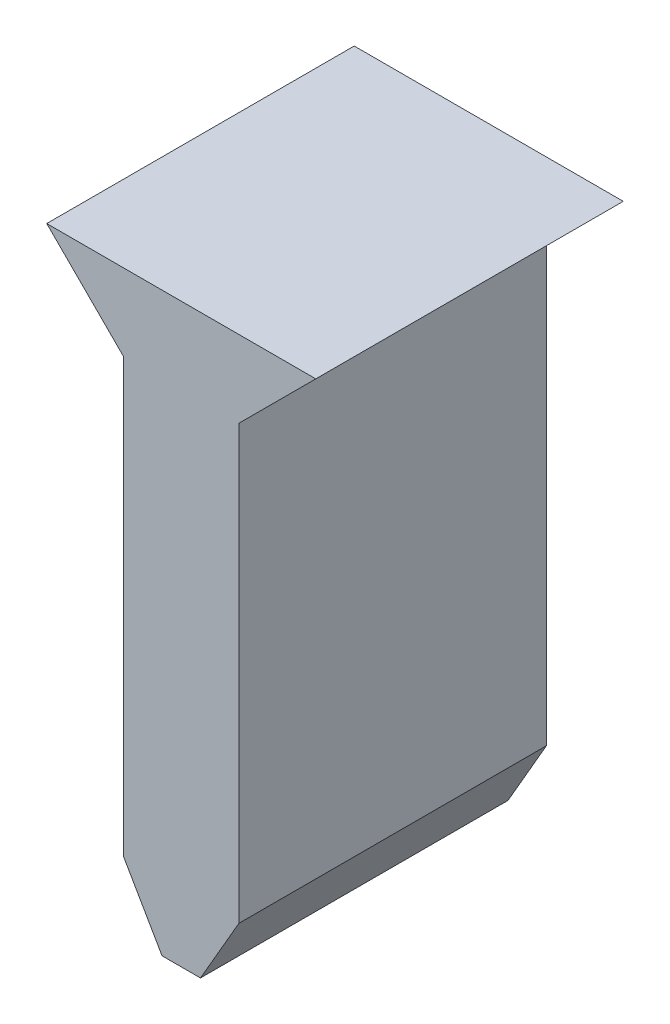
SolidWorks part; units mm, degrees
ref_plane "Front" through (0, 0, 0) normal (0, 0, 1) x (1, 0, 0)
ref_plane "Top" through (0, 0, 0) normal (0, 1, 0) x (1, 0, 0)
ref_plane "Right" through (0, 0, 0) normal (1, 0, 0) x (0, 0, -1)
sketch "Sketch1" plane through (0, 0, 0) normal (0, 0, 1) x (1, 0, 0)
  line L1 (-1.5, 6.5) -> (1.5, 6.5)
  line L2 (-1.5, 6.5) -> (-1.5, -6.5)
  line L3 (-1.5, -6.5) -> (1.5, -6.5)
  line L4 (1.5, 6.5) -> (1.5, -6.5)
  line L5 (-1.5, 6.5) -> (1.5, -6.5) construction
  line L6 (-1.5, -6.5) -> (1.5, 6.5) construction
  point P0 (0, 0)
  dimension "D1" = 13
  dimension "D2" = 3
extrude "Boss-Extrude1" add sketch "Sketch1" along normal mid plane 8
sketch "Sketch2" plane through (0, 0, 4) normal (0, 0, 1) x (1, 0, 0)
  line L0 (-1.5, 6.5) -> (-3.5, 8.5)
  line L1 (-3.5, 8.5) -> (3.5, 8.5)
  line L2 (3.5, 8.5) -> (1.5, 6.5)
  line L3 (1.5, 6.5) -> (-1.5, 6.5)
  point P3 (0, 8.5)
  dimension "D1" = 45
  dimension "D2" = 2
extrude "Boss-Extrude2" add sketch "Sketch2" against normal blind 8
chamfer "Chamfer1" distance 1 angle 60 2 edges at (-1.5, -6.5, 0) (1.5, -6.5, 0)
